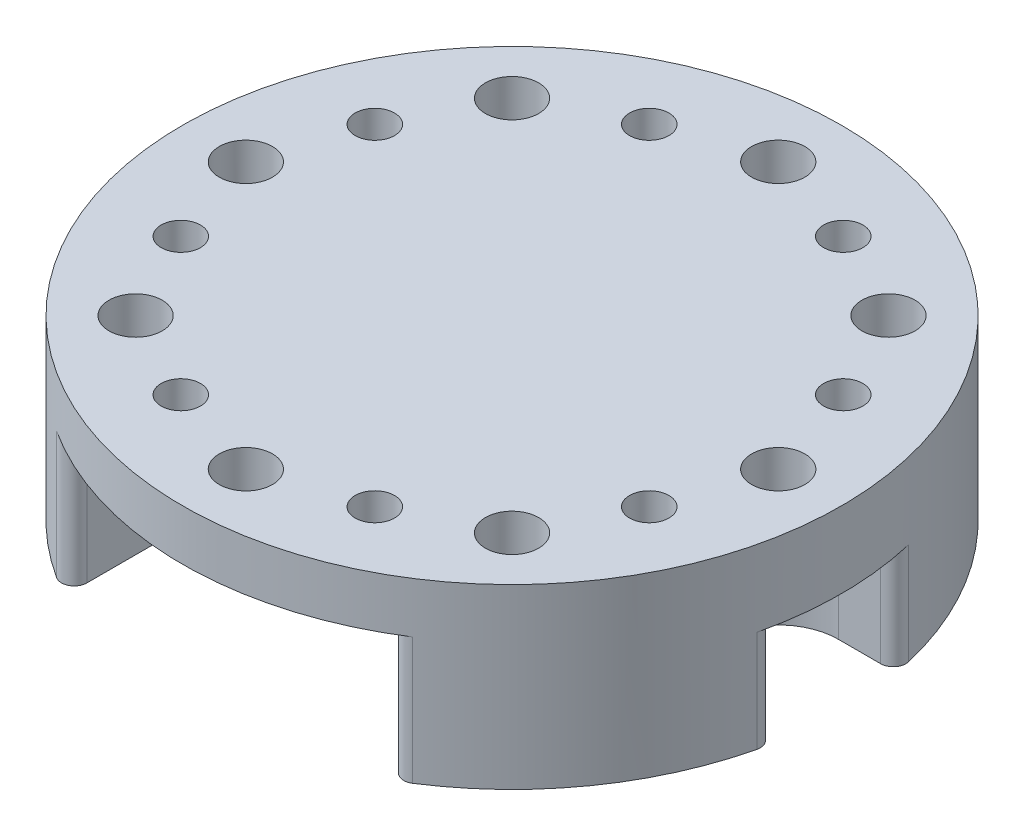
SolidWorks part; units mm, degrees
ref_plane "Front Plane" through (0, 0, 0) normal (0, 0, 1) x (1, 0, 0)
ref_plane "Top Plane" through (0, 0, 0) normal (0, 1, 0) x (1, 0, 0)
ref_plane "Right Plane" through (0, 0, 0) normal (1, 0, 0) x (0, 0, -1)
sketch "Sketch4" plane through (0, 0, 3) normal (0, -1, 0) x (1, 0, 0)
  line L0 (0, 18) -> (0, -3) construction
  line L1 (0, -3) -> (7.6537, 15.4776) construction
  circle A0 centre (0, 18) radius 2.1
  circle A1 centre (7.6537, 15.4776) radius 1.55
  circle A2 centre (14.8492, 11.8492) radius 2.1
  circle A3 centre (18.4776, 4.6537) radius 1.55
  circle A4 centre (21, -3) radius 2.1
  circle A5 centre (18.4776, -10.6537) radius 1.55
  circle A6 centre (14.8492, -17.8492) radius 2.1
  circle A7 centre (7.6537, -21.4776) radius 1.55
  circle A8 centre (0, -24) radius 2.1
  circle A9 centre (-7.6537, -21.4776) radius 1.55
  circle A10 centre (-14.8492, -17.8492) radius 2.1
  circle A11 centre (-18.4776, -10.6537) radius 1.55
  circle A12 centre (-21, -3) radius 2.1
  circle A13 centre (-18.4776, 4.6537) radius 1.55
  circle A14 centre (-14.8492, 11.8492) radius 2.1
  circle A15 centre (-7.6537, 15.4776) radius 1.55
  circle A16 centre (0, -3) radius 26
  point P37 (0, -3)
  dimension "D2" = 4.2
  dimension "D3" = 3.1
  dimension "D7" = 52
  dimension "D1" = 22.5
  dimension "D4" = 21
  dimension "D5" = 20
  dimension "D6" = 8
extrude "Boss-Extrude1" add sketch "Sketch4" along normal blind 4
sketch "Sketch5" plane through (0, -4, 0) normal (0, -1, 0) x (1, 0, 0)
  line L0 (-12.5, 22.798) -> (-12.5, -22.798)
  line L1 (12.5, -22.798) -> (12.5, 22.798)
  line L2 (12.5, 0) -> (-12.5, 0) construction
  circle A0 centre (0, 0) radius 26 construction
  arc A1 (-12.5, 22.798) -> (-12.5, -22.798) centre (0, 0) ccw
  arc A2 (12.5, -22.798) -> (12.5, 22.798) centre (0, 0) ccw
  circle A6 centre (-18.4776, 7.6537) radius 1.55
  circle A7 centre (-18.4776, 7.6537) radius 1.55
  circle A8 centre (-18.4776, -7.6537) radius 1.55
  circle A9 centre (-18.4776, -7.6537) radius 1.55
  circle A14 centre (18.4776, -7.6537) radius 1.55
  circle A15 centre (18.4776, -7.6537) radius 1.55
  circle A16 centre (18.4776, 7.6537) radius 1.55
  circle A17 centre (18.4776, 7.6537) radius 1.55
  circle A22 centre (14.8492, 14.8492) radius 2.1
  circle A23 centre (14.8492, 14.8492) radius 2.1
  circle A24 centre (21, 0) radius 2.1
  circle A25 centre (21, 0) radius 2.1
  circle A26 centre (14.8492, -14.8492) radius 2.1
  circle A27 centre (14.8492, -14.8492) radius 2.1
  circle A30 centre (-14.8492, -14.8492) radius 2.1
  circle A31 centre (-14.8492, -14.8492) radius 2.1
  circle A32 centre (-21, 0) radius 2.1
  circle A33 centre (-21, 0) radius 2.1
  circle A34 centre (-14.8492, 14.8492) radius 2.1
  circle A35 centre (-14.8492, 14.8492) radius 2.1
  point P9 (0, 0)
  dimension "D1" = 25
  dimension "D3" = 0
  dimension "D4" = 0
  dimension "D7" = 0
  dimension "D8" = 0
  dimension "D11" = 0
  dimension "D12" = 0
  dimension "D13" = 0
  dimension "D15" = 0
  dimension "D16" = 0
  dimension "D17" = 0
extrude "Boss-Extrude2" add sketch "Sketch5" along normal blind 10
sketch "Sketch6" plane through (0, -14, 0) normal (0, -1, 0) x (1, 0, 0)
  line L0 (21, 4.75) -> (25.5624, 4.75)
  line L1 (21, -4.75) -> (25.5624, -4.75)
  line L2 (0, 0) -> (0, -8.0384) construction
  line L3 (-21, -4.75) -> (-25.5624, -4.75)
  line L4 (-21, 4.75) -> (-25.5624, 4.75)
  arc A1 (21, 4.75) -> (21, -4.75) centre (21, 0) ccw
  arc A2 (12.5, -22.798) -> (12.5, 22.798) centre (0, 0) ccw construction
  arc A3 (25.5624, -4.75) -> (25.5624, 4.75) centre (0, 0) ccw
  arc A4 (-25.5624, -4.75) -> (-25.5624, 4.75) centre (0, 0) cw
  arc A5 (-21, 4.75) -> (-21, -4.75) centre (-21, 0) cw
  dimension "D1" = 9.5
extrude "Cut-Extrude1" cut sketch "Sketch6" against normal blind 8
fillet "Fillet1" radius 1 8 edges at (12.5, -9, 22.798) (12.5, -9, -22.798) (-12.5, -9, 22.798) (-12.5, -9, -22.798) (25.5624, -10, -4.75) (25.5624, -10, 4.75) (-25.5624, -10, -4.75) (-25.5624, -10, 4.75)
